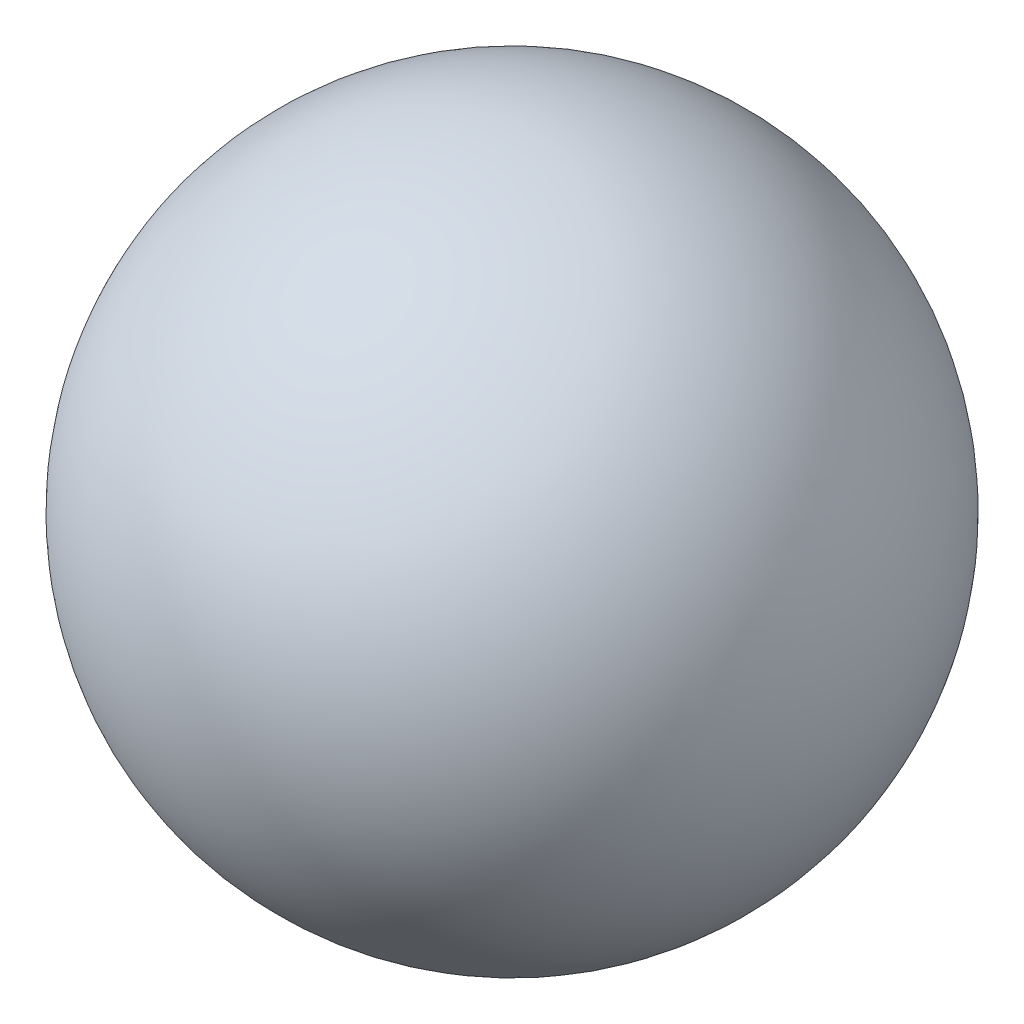
SolidWorks part; units mm, degrees
ref_plane "前视基准面" through (0, 0, 0) normal (0, 0, 1) x (1, 0, 0)
ref_plane "上视基准面" through (0, 0, 0) normal (0, 1, 0) x (1, 0, 0)
ref_plane "右视基准面" through (0, 0, 0) normal (1, 0, 0) x (0, 0, -1)
other "Configuration Table"
sketch "草图1" plane through (0, 0, 0) normal (0, 1, 0) x (1, 0, 0)
  line L0 (-31.7373, 0) -> (31.7373, 0)
  line L1 (0, 47.476) -> (0, -66.6069) construction
  arc A0 (31.7373, 0) -> (-31.7373, 0) centre (0, 0) ccw
revolve "旋转1" add sketch "草图1" angle 360 about L0
